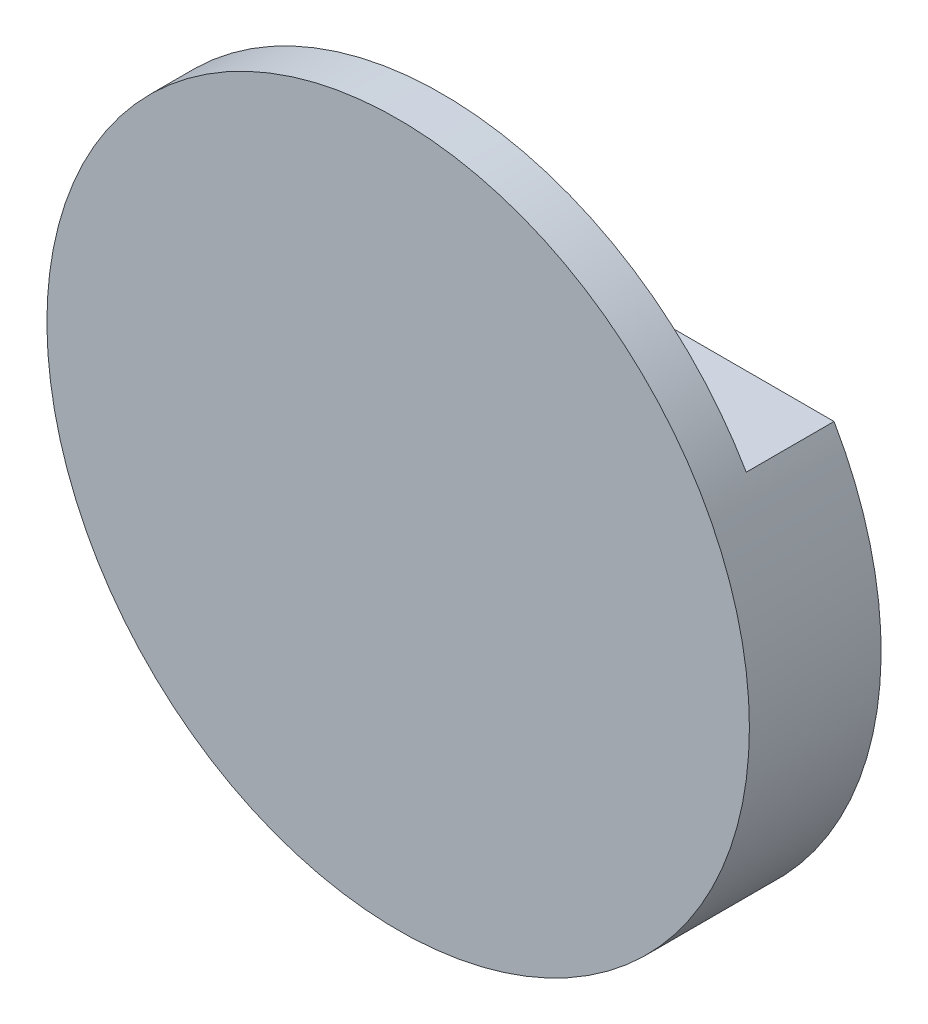
SolidWorks part; units mm, degrees
ref_plane "Front Plane" through (0, 0, 0) normal (0, 0, 1) x (1, 0, 0)
ref_plane "Top Plane" through (0, 0, 0) normal (0, 1, 0) x (1, 0, 0)
ref_plane "Right Plane" through (0, 0, 0) normal (1, 0, 0) x (0, 0, -1)
sketch "Sketch1" plane through (0, 0, 0) normal (0, 0, 1) x (1, 0, 0)
  line L0 (0, 0) -> (-1.5875, 1.5875) construction
  line L1 (-1.5875, 3.175) -> (1.5875, 3.175) construction
  line L2 (-1.5875, 3.175) -> (-1.5875, 1.5875)
  line L3 (-1.5875, -3.175) -> (1.5875, -3.175)
  line L4 (1.5875, 3.175) -> (1.5875, 1.5875)
  line L5 (-3.175, 1.5875) -> (-1.5875, 1.5875)
  line L6 (-3.175, 1.5875) -> (-3.175, -1.5875)
  line L7 (-3.175, -1.5875) -> (-1.5875, -1.5875)
  line L8 (3.175, 1.5875) -> (3.175, -1.5875)
  line L9 (-1.5875, 1.5875) -> (1.5875, 1.5875) construction
  line L10 (1.5875, 1.5875) -> (0, 0) construction
  line L11 (-1.5875, 3.175) -> (-5.4993, 3.175)
  line L12 (1.5875, -1.5875) -> (-1.5875, -1.5875) construction
  line L13 (-1.5875, -1.5875) -> (0, 0) construction
  line L14 (1.5875, 1.5875) -> (3.175, 1.5875)
  line L15 (-1.5875, -1.5875) -> (-1.5875, -3.175)
  line L16 (1.5875, -1.5875) -> (3.175, -1.5875)
  line L17 (1.5875, -1.5875) -> (1.5875, -3.175)
  line L18 (1.5875, 3.175) -> (5.4993, 3.175)
  arc A0 (-5.4993, 3.175) -> (5.4993, 3.175) centre (0, 0) ccw
  dimension "D2" = 6.35
  dimension "D1" = 3.175
  dimension "D3" = 6.35
extrude "Boss-Extrude1" add sketch "Sketch1" along normal blind 1.5875
sketch "Sketch2" plane through (0, 0, 1.5875) normal (0, 0, 1) x (1, 0, 0)
  circle A1 centre (0, 0) radius 6.35
  arc A3 (-5.4993, 3.175) -> (5.4993, 3.175) centre (0, 0) ccw construction
extrude "Boss-Extrude2" add sketch "Sketch2" along normal blind 0.7937
fillet "Fillet1" radius 0.5 4 edges at (-1.5875, 1.5875, 0.7937) (1.5875, 1.5875, 0.7937) (1.5875, -1.5875, 0.7937) (-1.5875, -1.5875, 0.7937)
